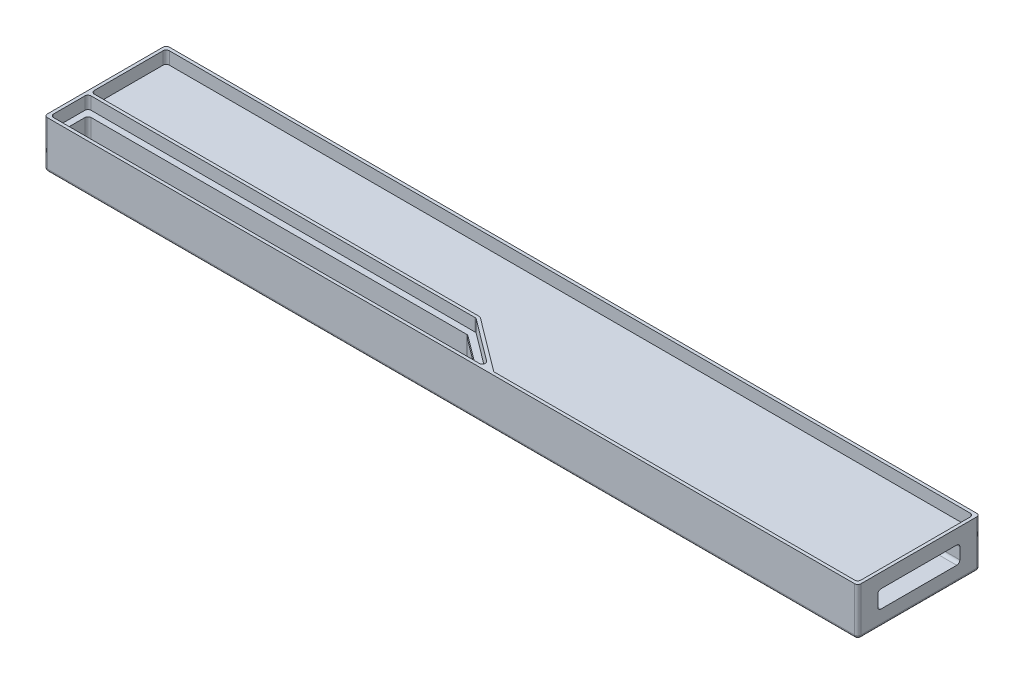
SolidWorks part; units mm, degrees
ref_plane "Спереди" through (0, 0, 0) normal (0, 0, 1) x (1, 0, 0)
ref_plane "Сверху" through (0, 0, 0) normal (0, 1, 0) x (1, 0, 0)
ref_plane "Справа" through (0, 0, 0) normal (1, 0, 0) x (0, 0, -1)
sketch "Эскиз1" plane through (0, 0, 0) normal (0, 1, 0) x (1, 0, 0)
  line L1 (-64.5, 9.75) -> (64.5, 9.75)
  line L2 (-65, 9.25) -> (-65, -9.25)
  line L3 (-64.5, -9.75) -> (64.5, -9.75)
  line L4 (65, 9.25) -> (65, -9.25)
  line L5 (-65, 9.75) -> (65, -9.75) construction
  line L6 (-65, -9.75) -> (65, 9.75) construction
  arc A0 (64.5, 9.75) -> (65, 9.25) centre (64.5, 9.25) cw
  arc A1 (64.5, -9.75) -> (65, -9.25) centre (64.5, -9.25) ccw
  arc A2 (-64.5, -9.75) -> (-65, -9.25) centre (-64.5, -9.25) cw
  arc A3 (-64.5, 9.75) -> (-65, 9.25) centre (-64.5, 9.25) ccw
  point P0 (0, 0)
  dimension "D3" = 0.5
  dimension "D1" = 130
  dimension "D2" = 19.5
extrude "Бобышка-Вытянуть1" add sketch "Эскиз1" along normal blind 7.6
sketch "Эскиз2" plane through (0, 7.6, 0) normal (0, 1, 0) x (1, 0, 0)
  line L1 (-64, -3.25) -> (-2.6667, -3.25)
  line L2 (-64.5, -3.75) -> (-64.5, -8.75)
  line L3 (5.5, -9.25) -> (-2.5, -3.25) construction
  line L4 (64.5, 9.75) -> (-64.5, 9.75) construction
  line L6 (-64.5, -3.25) -> (-2.5, -3.25) construction
  line L7 (4.3, -8.35) -> (-2.3667, -3.35)
  line L8 (-64, -9.25) -> (4, -9.25)
  line L9 (-64.5, -3.25) -> (-64.5, -9.25) construction
  line L10 (-64, 9.25) -> (64, 9.25)
  line L11 (64.5, -8.75) -> (64.5, 8.75)
  line L12 (-64.5, -2.25) -> (-64.5, 8.75)
  line L13 (-64, -2.75) -> (-2.5, -2.75)
  line L14 (6.2, -9.15) -> (-2.2, -2.85)
  line L15 (6.5, -9.25) -> (64, -9.25)
  line L16 (7, -9.75) -> (-2.3333, -2.75) construction
  line L17 (-65, -2.75) -> (-2.3333, -2.75) construction
  line L18 (-65, -2.75) -> (-65, -9.75) construction
  line L19 (-65, -9.75) -> (-2.5, -9.75) construction
  line L20 (-2.5, -9.75) -> (7, -9.75) construction
  line L21 (-64.5, -9.25) -> (-2.5, -9.25) construction
  line L22 (-2.5, -9.25) -> (5.5, -9.25) construction
  line L23 (65, -9.25) -> (65, 9.25) construction
  arc A0 (64.5, -8.75) -> (64, -9.25) centre (64, -8.75) cw
  arc A1 (64.5, 8.75) -> (64, 9.25) centre (64, 8.75) ccw
  arc A2 (-64, 9.25) -> (-64.5, 8.75) centre (-64, 8.75) ccw
  arc A3 (-64.5, -2.25) -> (-64, -2.75) centre (-64, -2.25) ccw
  arc A4 (6.5, -9.25) -> (6.2, -9.15) centre (6.5, -8.75) cw
  arc A5 (-2.5, -2.75) -> (-2.2, -2.85) centre (-2.5, -3.25) cw
  arc A6 (-2.3667, -3.35) -> (-2.6667, -3.25) centre (-2.6667, -3.75) ccw
  arc A7 (-64, -9.25) -> (-64.5, -8.75) centre (-64, -8.75) cw
  arc A8 (-64.5, -3.75) -> (-64, -3.25) centre (-64, -3.75) cw
  arc A9 (4, -9.25) -> (4.3, -8.35) centre (4, -8.75) ccw
  point P22 (64.5, -9.25)
  point P27 (-64.5, 9.25)
  point P32 (6.3333, -9.25)
  point P39 (-2.5, -3.25)
  dimension "D2" = 0.5
  dimension "D1" = 0.5
  dimension "D3" = 129
  dimension "D4" = 12
  dimension "D5" = 62
  dimension "D6" = 0.5
  dimension "D7" = 58.1667
  dimension "D8" = 0.5
  dimension "D9" = 18.5
extrude "Вырез-Вытянуть1" cut sketch "Эскиз2" against normal blind 2
sketch "Эскиз6" plane through (0, 5.6, 0) normal (0, 1, 0) x (1, 0, 0)
  line L0 (-64.5, -9.75) -> (64.5, -9.75) construction
  line L1 (-64, -3.2382) -> (-2.6618, -3.2382)
  line L2 (-64.5, -3.7382) -> (-64.5, -8.75)
  line L3 (-63, -4.2382) -> (-2.9952, -4.2382)
  line L4 (-65, 9.25) -> (-65, -9.25) construction
  line L5 (1.3206, -7.35) -> (-2.6952, -4.3382)
  line L6 (-63, -8.25) -> (1.0206, -8.25)
  line L7 (4.3206, -8.35) -> (-2.3618, -3.3382)
  line L8 (-64, -9.25) -> (4.0206, -9.25)
  line L9 (-63.5, -4.7382) -> (-63.5, -7.75)
  line L10 (-63.5, -8.25) -> (2.5206, -8.25) construction
  line L11 (2.5206, -8.25) -> (-2.8285, -4.2382) construction
  line L12 (-63.5, -4.2382) -> (-2.8285, -4.2382) construction
  line L13 (-63.5, -4.2382) -> (-63.5, -8.25) construction
  arc A0 (-63, -8.25) -> (-63.5, -7.75) centre (-63, -7.75) cw
  arc A1 (-2.6952, -4.3382) -> (-2.9952, -4.2382) centre (-2.9952, -4.7382) ccw
  arc A2 (-63.5, -4.7382) -> (-63, -4.2382) centre (-63, -4.7382) cw
  arc A4 (1.0206, -8.25) -> (1.3206, -7.35) centre (1.0206, -7.75) ccw
  arc A6 (-2.3618, -3.3382) -> (-2.6618, -3.2382) centre (-2.6618, -3.7382) ccw
  arc A7 (-64, -9.25) -> (-64.5, -8.75) centre (-64, -8.75) cw
  arc A8 (-64.5, -3.7382) -> (-64, -3.2382) centre (-64, -3.7382) cw
  arc A9 (4.0206, -9.25) -> (4.3206, -8.35) centre (4.0206, -8.75) ccw
  arc A10 (2.5206, -8.25) -> (2.5206, -8.25) centre (2.5206, -8.25) ccw construction
  arc A11 (-2.8285, -4.2382) -> (-2.8285, -4.2382) centre (-2.8285, -4.2382) ccw construction
  arc A12 (-63.5, -8.25) -> (-63.5, -8.25) centre (-63.5, -8.25) cw construction
  arc A13 (-63.5, -4.2382) -> (-63.5, -4.2382) centre (-63.5, -4.2382) cw construction
  point P39 (-2.4952, -3.2382)
  dimension "D2" = 1
  dimension "D4" = 0.5
  dimension "D1" = 0.5
  dimension "D3" = 0.5
extrude "Вырез-Вытянуть2" cut sketch "Эскиз6" against normal through all contours L6 A4 L5 A1 L3 A2 L9 A0
sketch "Эскиз7" plane through (0, 0, 0) normal (0, -1, 0) x (1, 0, 0)
  line L0 (-64.5, 9.75) -> (64.5, 9.75) construction
  line L1 (-63, 4.25) -> (59.5, 4.25)
  line L2 (-63.5, 4.75) -> (-63.5, 7.75)
  line L3 (-63, 8.25) -> (59.5, 8.25)
  line L4 (60, 4.75) -> (60, 7.75)
  line L5 (-65, -9.25) -> (-65, 9.25) construction
  line L6 (64.5, -9.75) -> (-64.5, -9.75) construction
  line L7 (59.5, -7.75) -> (41, -7.75)
  line L8 (60, -7.25) -> (60, 1.75)
  line L9 (59.5, 2.25) -> (41, 2.25)
  line L10 (40.5, -7.25) -> (40.5, 1.75)
  line L11 (65, 9.25) -> (65, -9.25) construction
  line L13 (-61.74, -8.15) -> (-61.76, -8.15)
  line L14 (-60, -6.41) -> (-60, 1.11)
  line L15 (-61.74, 2.85) -> (-61.76, 2.85)
  line L16 (-63.5, -6.41) -> (-63.5, 1.11)
  arc A0 (-63.5, 7.75) -> (-63, 8.25) centre (-63, 7.75) cw
  arc A1 (-63.5, 4.75) -> (-63, 4.25) centre (-63, 4.75) ccw
  arc A2 (60, 7.75) -> (59.5, 8.25) centre (59.5, 7.75) ccw
  arc A3 (59.5, 4.25) -> (60, 4.75) centre (59.5, 4.75) ccw
  arc A4 (60, 1.75) -> (59.5, 2.25) centre (59.5, 1.75) ccw
  arc A5 (41, 2.25) -> (40.5, 1.75) centre (41, 1.75) ccw
  arc A6 (40.5, -7.25) -> (41, -7.75) centre (41, -7.25) ccw
  arc A7 (59.5, -7.75) -> (60, -7.25) centre (59.5, -7.25) ccw
  arc A8 (-60, 1.11) -> (-61.74, 2.85) centre (-61.74, 1.11) ccw
  arc A9 (-61.76, 2.85) -> (-63.5, 1.11) centre (-61.76, 1.11) ccw
  arc A10 (-63.5, -6.41) -> (-61.76, -8.15) centre (-61.76, -6.41) ccw
  arc A11 (-61.74, -8.15) -> (-60, -6.41) centre (-61.74, -6.41) ccw
  point P10 (-63.5, 8.25)
  point P13 (-63.5, 4.25)
  point P16 (60, 8.25)
  point P29 (60, 2.25)
  point P34 (40.5, -7.75)
  point P37 (60, -7.75)
  point P44 (-60, 2.85)
  point P49 (-63.5, -8.15)
  point P52 (-60, -8.15)
  dimension "D5" = 0.5
  dimension "D10" = 0.5
  dimension "D15" = 1.74
  dimension "D1" = 4
  dimension "D2" = 1.5
  dimension "D3" = 1.5
  dimension "D4" = 123.5
  dimension "D6" = 19.5
  dimension "D7" = 10
  dimension "D8" = 2
  dimension "D9" = 5
  dimension "D11" = 3.5
  dimension "D12" = 11
  dimension "D13" = 1.6
  dimension "D14" = 1.5
extrude "Вырез-Вытянуть3" cut sketch "Эскиз7" against normal blind 1.6
sketch "Эскиз8" plane through (0, 1.6, 0) normal (0, -1, 0) x (1, 0, 0)
  line L0 (-64.5, 9.75) -> (64.5, 9.75) construction
  line L1 (-63, 8.25) -> (40, 8.25)
  line L2 (-63.5, 7.75) -> (-63.5, 4.75)
  line L3 (-63, 4.25) -> (40, 4.25)
  line L4 (40.5, 7.75) -> (40.5, 4.75)
  line L5 (-65, -9.25) -> (-65, 9.25) construction
  arc A0 (-63, 4.25) -> (-63.5, 4.75) centre (-63, 4.75) cw
  arc A1 (-63.5, 7.75) -> (-63, 8.25) centre (-63, 7.75) cw
  arc A2 (40, 8.25) -> (40.5, 7.75) centre (40, 7.75) cw
  arc A3 (40, 4.25) -> (40.5, 4.75) centre (40, 4.75) ccw
  point P10 (-63.5, 4.25)
  point P13 (-63.5, 8.25)
  point P16 (40.5, 8.25)
  dimension "D5" = 0.5
  dimension "D1" = 4
  dimension "D2" = 1.5
  dimension "D3" = 1.5
  dimension "D4" = 104
extrude "Вырез-Вытянуть4" cut sketch "Эскиз8" against normal blind 3.3
sketch "Эскиз9" plane through (65, 0, 0) normal (1, 0, 0) x (0, 0, -1)
  line L0 (-9.75, 7.6) -> (-9.75, 0) construction
  line L1 (-6.05, 5.3) -> (6.05, 5.3)
  line L2 (-6.55, 4.8) -> (-6.55, 3)
  line L3 (-6.05, 2.5) -> (6.05, 2.5)
  line L4 (6.55, 4.8) -> (6.55, 3)
  line L5 (-9.25, 7.6) -> (9.25, 7.6) construction
  arc A0 (6.05, 5.3) -> (6.55, 4.8) centre (6.05, 4.8) cw
  arc A1 (6.55, 3) -> (6.05, 2.5) centre (6.05, 3) cw
  arc A2 (-6.05, 2.5) -> (-6.55, 3) centre (-6.05, 3) cw
  arc A3 (-6.05, 5.3) -> (-6.55, 4.8) centre (-6.05, 4.8) ccw
  point P10 (6.55, 5.3)
  point P15 (-6.55, 2.5)
  point P18 (-6.55, 5.3)
  dimension "D5" = 0.5
  dimension "D1" = 3.2
  dimension "D2" = 2.3
  dimension "D3" = 13.1
  dimension "D4" = 2.8
extrude "Вырез-Вытянуть5" cut sketch "Эскиз9" against normal blind 10
fillet "Скругление1" radius 0.5 8 edges at (64.8536, 0, 9.6036) (64.8536, 0, -9.6036) (-64.8536, 0, 9.6036) (-64.8536, 0, -9.6036) (-65, 0, 0) (0, 0, 9.75) (65, 0, 0) (0, 0, -9.75)
